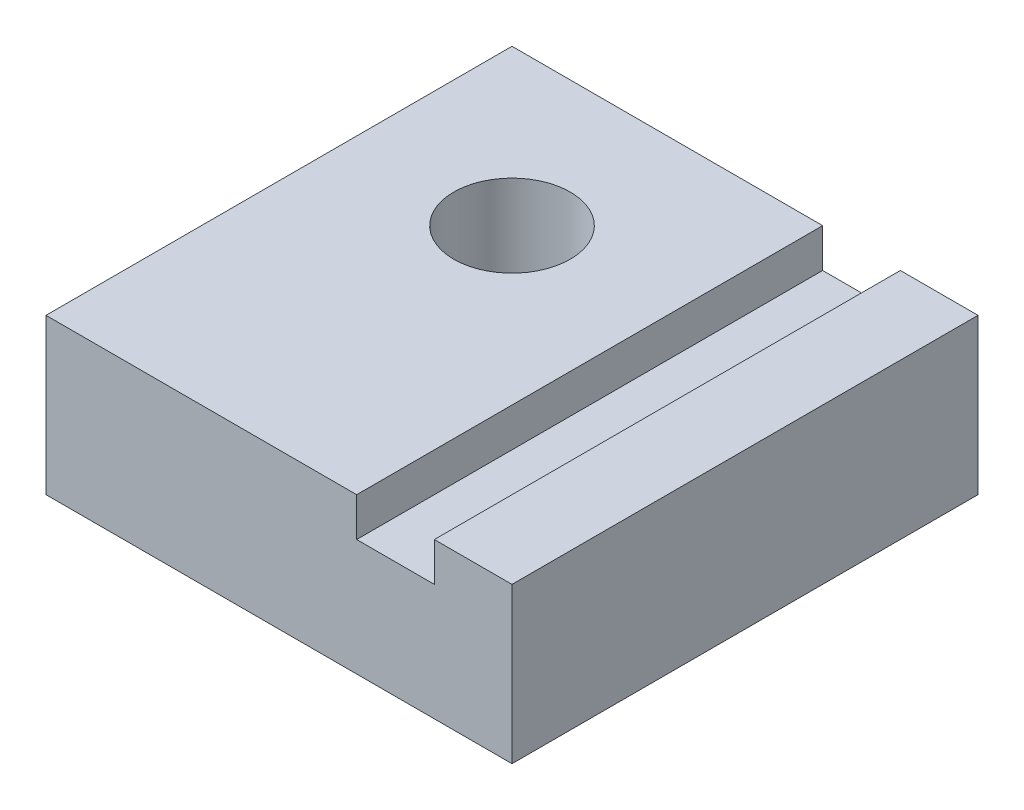
SolidWorks part; units mm, degrees
material "AISI 304"
ref_plane "Front Plane" through (0, 0, 0) normal (0, 0, 1) x (1, 0, 0)
ref_plane "Top Plane" through (0, 0, 0) normal (0, 1, 0) x (1, 0, 0)
ref_plane "Right Plane" through (0, 0, 0) normal (1, 0, 0) x (0, 0, -1)
sketch "Sketch1" plane through (0, 0, 0) normal (0, 0, 1) x (1, 0, 0)
  line L0 (0, 38.2363) -> (0, -28.9669) construction
  line L1 (-57.15, 0) -> (19.05, 0)
  line L2 (-57.15, 0) -> (-57.15, 25.4)
  line L3 (-57.15, 25.4) -> (-6.35, 25.4)
  line L4 (-6.35, 25.4) -> (-6.35, 19.05)
  line L5 (-6.35, 19.05) -> (6.35, 19.05)
  line L6 (6.35, 19.05) -> (6.35, 25.4)
  line L7 (6.35, 25.4) -> (19.05, 25.4)
  line L8 (19.05, 25.4) -> (19.05, 0)
  dimension "D1" = 76.2
  dimension "D2" = 25.4
  dimension "D3" = 6.35
  dimension "D4" = 12.7
  dimension "D5" = 12.7
extrude "Boss-Extrude1" add sketch "Sketch1" along normal blind 76.2
sketch "Sketch2" plane through (0, 25.4, 0) normal (0, 1, 0) x (1, 0, 0)
  line L0 (-6.35, 0) -> (-57.15, 0) construction
  line L1 (-57.15, -76.2) -> (-57.15, 0) construction
  circle A0 centre (-31.75, -25.4) radius 9.525
  dimension "D1" = 25.4
  dimension "D3" = 19.05
  dimension "D2" = 25.4
extrude "Cut-Extrude1" cut sketch "Sketch2" against normal through all
